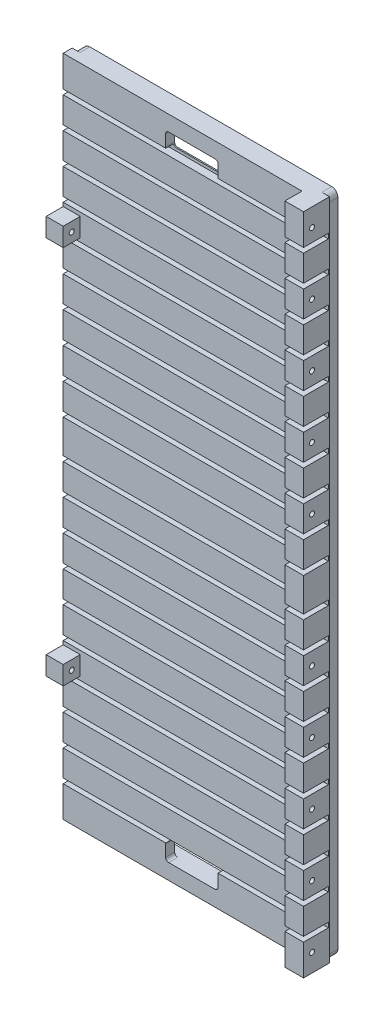
SolidWorks part; units mm, degrees
ref_plane "Front Plane" through (0, 0, 0) normal (0, 0, 1) x (1, 0, 0)
ref_plane "Top Plane" through (0, 0, 0) normal (0, 1, 0) x (1, 0, 0)
ref_plane "Right Plane" through (0, 0, 0) normal (1, 0, 0) x (0, 0, -1)
sketch "Sketch1" plane through (0, 0, 0) normal (0, 0, 1) x (1, 0, 0)
  line L1 (-41.5, -107) -> (41.5, -107)
  line L2 (-41.5, -107) -> (-41.5, 107)
  line L3 (-41.5, 107) -> (41.5, 107)
  line L4 (41.5, -107) -> (41.5, 107)
  line L5 (-41.5, -107) -> (41.5, 107) construction
  line L6 (-41.5, 107) -> (41.5, -107) construction
  point P0 (0, 0)
  dimension "D1" = 83
  dimension "D2" = 214
extrude "Boss-Extrude1" add sketch "Sketch1" along normal blind 8.4
sketch "Sketch2" plane through (0, 107, 0) normal (0, 1, 0) x (1, 0, 0)
  line L0 (41.5, -8.4) -> (41.5, 0) construction
  line L1 (-41.5, -8.4) -> (35.5, -8.4)
  line L2 (-41.5, -8.4) -> (-41.5, -2.9)
  line L3 (-41.5, -2.9) -> (35.5, -2.9)
  line L4 (35.5, -8.4) -> (35.5, -2.9)
  dimension "D1" = 5.5
  dimension "D2" = 6
extrude "Cut-Extrude1" cut sketch "Sketch2" against normal through all
sketch "Sketch3" plane through (41.5, 0, 0) normal (1, 0, 0) x (0, 0, -1)
  line L0 (-8.4, -107) -> (-8.4, 107) construction
  line L1 (-8.4, 97) -> (-0.4, 97)
  line L2 (-8.4, 97) -> (-8.4, 95.4)
  line L3 (-8.4, 95.4) -> (-0.4, 95.4)
  line L4 (-0.4, 97) -> (-0.4, 95.4)
  line L5 (-8.4, 107) -> (0, 107) construction
  dimension "D1" = 1.6
  dimension "D2" = 8
  dimension "D3" = 10
extrude "Cut-Extrude2" cut sketch "Sketch3" against normal through all
pattern_linear "LPattern1" count 10 spacing 10 along (0, -1, 0) of "Cut-Extrude2"
mirror "Mirror1" about plane through (0, 0, 0) normal (0, 1, 0) of "LPattern1", "Cut-Extrude2"
sketch "Sketch4" plane through (0, 0, 0) normal (0, 0, -1) x (-1, 0, 0)
  line L0 (-41.5, 107) -> (41.5, 107) construction
  line L1 (-39, 107) -> (39, 107)
  line L2 (-41, 105) -> (-41, -105)
  line L3 (-39, -107) -> (39, -107)
  line L4 (41, 105) -> (41, -105)
  line L5 (-33.5, -102) -> (33.5, -102)
  line L6 (-35.5, -100) -> (-35.5, 100)
  line L7 (-33.5, 102) -> (33.5, 102)
  line L8 (35.5, -100) -> (35.5, 100)
  line L9 (-35.5, -102) -> (35.5, 102) construction
  line L10 (-35.5, 102) -> (35.5, -102) construction
  line L11 (41.5, -107) -> (-41.5, -107) construction
  arc A0 (-41, -105) -> (-39, -107) centre (-39, -105) ccw
  arc A1 (39, -107) -> (41, -105) centre (39, -105) ccw
  arc A2 (39, 107) -> (41, 105) centre (39, 105) cw
  arc A3 (-39, 107) -> (-41, 105) centre (-39, 105) ccw
  arc A4 (33.5, -102) -> (35.5, -100) centre (33.5, -100) ccw
  arc A5 (-33.5, -102) -> (-35.5, -100) centre (-33.5, -100) cw
  arc A6 (-35.5, 100) -> (-33.5, 102) centre (-33.5, 100) cw
  arc A7 (33.5, 102) -> (35.5, 100) centre (33.5, 100) cw
  point P10 (41.5, -107)
  point P15 (-41.5, 107)
  point P16 (0, 0)
  dimension "D1" = 2
  dimension "D4" = 2
  dimension "D2" = 5
  dimension "D3" = 5.5
  dimension "D5" = 41
  dimension "D6" = 41
extrude "Boss-Extrude2" add sketch "Sketch4" along normal blind 3.18
sketch "Sketch5" plane through (0, 0, 2.9) normal (0, 0, 1) x (1, 0, 0)
  line L0 (-41.5, 57) -> (-41.5, 65.4) construction
  line L1 (-36, 58.2) -> (-41.5, 58.2)
  line L2 (-36, 58.2) -> (-36, 64.2)
  line L3 (-36, 64.2) -> (-41.5, 64.2)
  line L4 (-41.5, 58.2) -> (-41.5, 64.2)
  line L5 (-36, 58.2) -> (-41.5, 64.2) construction
  line L6 (-36, 64.2) -> (-41.5, 58.2) construction
  line L8 (35.5, 65.4) -> (-41.5, 65.4) construction
  point P0 (-38.75, 61.2)
  dimension "D1" = 6
  dimension "D2" = 5.5
  dimension "D3" = 4.2
extrude "Boss-Extrude3" add sketch "Sketch5" along normal blind 5.5
mirror "Mirror2" about plane through (0, 0, 0) normal (0, 1, 0) of "Boss-Extrude3"
sketch "Sketch6" plane through (0, 0, 0) normal (0, 0, -1) x (-1, 0, 0)
  line L0 (33.5, 102) -> (-33.5, 102) construction
  line L1 (-7.475, 96.3) -> (7.475, 96.3)
  line L2 (-8.475, 97.3) -> (-8.475, 101)
  line L3 (-7.475, 102) -> (7.475, 102)
  line L4 (8.475, 97.3) -> (8.475, 101)
  line L5 (-8.475, 96.3) -> (8.475, 102) construction
  line L6 (-8.475, 102) -> (8.475, 96.3) construction
  arc A0 (-8.475, 101) -> (-7.475, 102) centre (-7.475, 101) cw
  arc A1 (7.475, 102) -> (8.475, 101) centre (7.475, 101) cw
  arc A2 (7.475, 96.3) -> (8.475, 97.3) centre (7.475, 97.3) ccw
  arc A3 (-7.475, 96.3) -> (-8.475, 97.3) centre (-7.475, 97.3) cw
  point P0 (0, 99.15)
  dimension "D3" = 1
  dimension "D1" = 5.7
  dimension "D2" = 16.95
extrude "Cut-Extrude3" cut sketch "Sketch6" against normal through all
mirror "Mirror3" about plane through (0, 0, 0) normal (0, 1, 0) of "Cut-Extrude3"
hole_wizard "M2x0.4 Tapped Hole1" positions "Sketch8" profile "Sketch7" tap size "M2x0.4" standard "ANSI Metric" end condition through all
sketch "Sketch8" plane through (41.5, 0, 0) normal (1, 0, 0) x (0, 0, -1)
  line L0 (-8.4, 97) -> (-8.4, 107) construction
  line L1 (-8.4, 107) -> (0, 107) construction
  line L2 (0, 0) -> (-25.7972, 0) construction
  line L3 (0, -107) -> (0, 107) construction
  point P0 (-5.65, 101.2)
  point P16 (-5.65, 81.2)
  point P17 (-5.65, 61.2)
  point P18 (-5.65, 41.2)
  point P19 (-5.65, 21.2)
  point P34 (-5.65, -101.2)
  point P35 (-5.65, -81.2)
  point P36 (-5.65, -61.2)
  point P37 (-5.65, -41.2)
  point P38 (-5.65, -21.2)
  dimension "D1" = 2.75
  dimension "D2" = 5.8
  dimension "D3" = 5
sketch "Sketch7" plane through (41.5, 101.2, 5.65) normal (0, 1, 0) x (0, 0, -1)
  line L0 (0, 0) -> (0, 83)
  line L1 (0, 83) -> (0.8, 83)
  line L2 (0.8, 83) -> (0.8, 0)
  line L5 (0.8, 0) -> (0, 0)
  line L11 (0, -6.35) -> (0, 107.95) construction
  dimension "Thread Major Dia." = 1.6
  dimension "Thru Tap Drill Depth" = 83
hole_wizard "M2x0.4 Tapped Hole2" positions "Sketch10" profile "Sketch11" tap size "M2x0.4" standard "ANSI Metric"
sketch "Sketch10" plane through (0, 0, -3.18) normal (0, 0, -1) x (-1, 0, 0)
  line L0 (39, 107) -> (-39, 107) construction
  line L1 (-41, 105) -> (-41, -105) construction
  line L3 (-35.5, 0) -> (35.5, 0) construction
  line L4 (-35.5, 100) -> (-35.5, -100) construction
  line L5 (35.5, -100) -> (35.5, 100) construction
  point P0 (-37.5, 101.2)
  point P15 (37.5, 101.2)
  point P16 (37.5, 81.2)
  point P17 (37.5, 61.2)
  point P18 (37.5, 41.2)
  point P19 (37.5, 21.2)
  point P20 (-37.5, 81.2)
  point P21 (-37.5, 61.2)
  point P22 (-37.5, 41.2)
  point P23 (-37.5, 21.2)
  point P32 (37.5, -101.2)
  point P33 (-37.5, -21.2)
  point P34 (-37.5, -41.2)
  point P35 (-37.5, -61.2)
  point P36 (-37.5, -81.2)
  point P37 (37.5, -21.2)
  point P38 (37.5, -41.2)
  point P39 (37.5, -61.2)
  point P40 (37.5, -81.2)
  point P41 (-37.5, -101.2)
  dimension "D1" = 5.8
  dimension "D2" = 3.5
  dimension "D5" = 2
  dimension "D3" = 5
sketch "Sketch11" plane through (37.5, 101.2, -3.18) normal (1, 0, 0) x (0, 1, 0)
  line L0 (0, 0) -> (0, 4.4807)
  line L1 (0, 4.4807) -> (0.8, 4)
  line L2 (0.8, 4) -> (0.8, 0)
  line L5 (0.8, 0) -> (0, 0)
  line L10 (0, 4.4807) -> (-0.8, 4) construction
  line L11 (0, -6.35) -> (0, 107.95) construction
  dimension "Tap Drill Dia." = 1.6
  dimension "Tap Drill Depth" = 4
  dimension "Drill Angle" = 118
